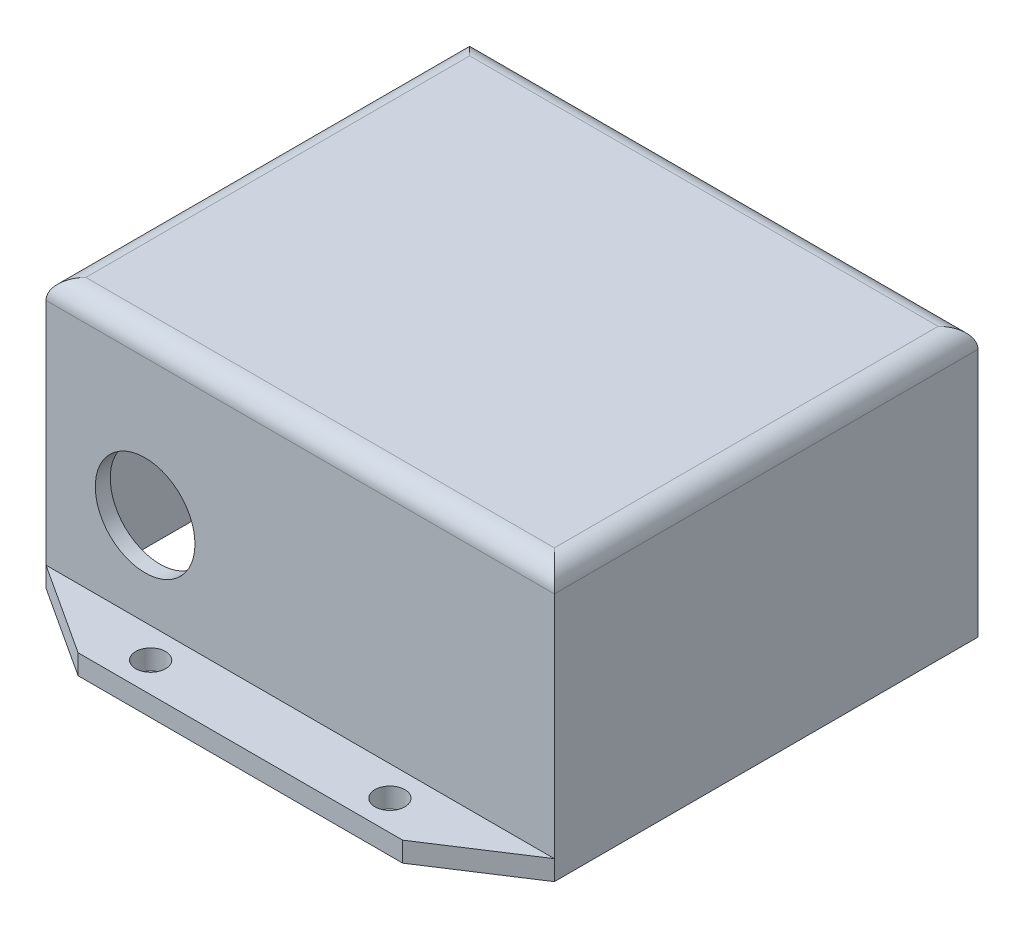
SolidWorks part; units mm, degrees
ref_plane "前视基准面" through (0, 0, 0) normal (0, 0, 1) x (1, 0, 0)
ref_plane "上视基准面" through (0, 0, 0) normal (0, 1, 0) x (1, 0, 0)
ref_plane "右视基准面" through (0, 0, 0) normal (1, 0, 0) x (0, 0, -1)
sketch "草图1" plane through (0, 0, 0) normal (0, 1, 0) x (1, 0, 0)
  line L0 (-51, -42.5) -> (51, -42.5) construction
  line L1 (-48, -39.5) -> (48, -39.5) construction
  line L2 (-48, -39.5) -> (-48, 39.5) construction
  line L3 (-48, 39.5) -> (48, 39.5) construction
  line L4 (48, -39.5) -> (48, 39.5) construction
  line L5 (-48, -39.5) -> (48, 39.5) construction
  line L6 (-48, 39.5) -> (48, -39.5) construction
  line L7 (51, -42.5) -> (51, 42.5)
  line L9 (-51, -42.5) -> (-51, 42.5)
  line L10 (-32.5609, 54.5) -> (32.5609, 54.5)
  line L11 (-32.5609, -54.5) -> (32.5609, -54.5)
  line L12 (-51, 42.5) -> (-32.5609, 54.5)
  line L13 (51, 42.5) -> (32.5609, 54.5)
  line L14 (-51, -42.5) -> (-32.5609, -54.5)
  line L15 (51, -42.5) -> (32.5609, -54.5)
  line L16 (0, 54.5) -> (0, 42.5) construction
  line L17 (0, -42.5) -> (0, -54.5) construction
  line L18 (-51, 42.5) -> (51, 42.5) construction
  circle A0 centre (-24, 48.5) radius 3
  circle A1 centre (24, 48.5) radius 3
  circle A2 centre (24, -48.5) radius 3
  circle A3 centre (-24, -48.5) radius 3
  point P0 (0, 0)
  dimension "D3" = 3
  dimension "D7" = 6
  dimension "D1" = 96
  dimension "D2" = 79
  dimension "D6" = 22
  dimension "D8" = 24
  dimension "D9" = 24
  dimension "D10" = 24
  dimension "D11" = 24
extrude "凸台-拉伸1" add sketch "草图1" along normal blind 4
sketch "草图2" plane through (0, 4, 0) normal (0, 1, 0) x (1, 0, 0)
  line L7 (-51, -42.5) -> (51, -42.5)
  line L8 (-51, -42.5) -> (-51, 42.5)
  line L9 (-51, 42.5) -> (51, 42.5)
  line L10 (51, -42.5) -> (51, 42.5)
  point P0 (0, 0)
  point P7 (0, 0)
extrude "凸台-拉伸2" add sketch "草图2" along normal blind 50
sketch "草图4" plane through (0, 0, 0) normal (0, -1, 0) x (1, 0, 0)
  line L1 (-48, -39.5) -> (48, -39.5)
  line L2 (-48, -39.5) -> (-48, 39.5)
  line L3 (-48, 39.5) -> (48, 39.5)
  line L4 (48, -39.5) -> (48, 39.5)
  line L5 (-48, -39.5) -> (48, 39.5) construction
  line L6 (-48, 39.5) -> (48, -39.5) construction
extrude "切除-拉伸3" cut sketch "草图4" against normal blind 50
fillet "圆角1" radius 4 4 edges at (0, 54, -42.5) (51, 54, 0) (0, 54, 42.5) (-51, 54, 0)
sketch "草图5" plane through (0, 0, 42.5) normal (0, 0, 1) x (1, 0, 0)
  circle A0 centre (-31.1112, 22.5989) radius 10
  dimension "D1" = 20
extrude "切除-拉伸4" cut sketch "草图5" against normal up to next
